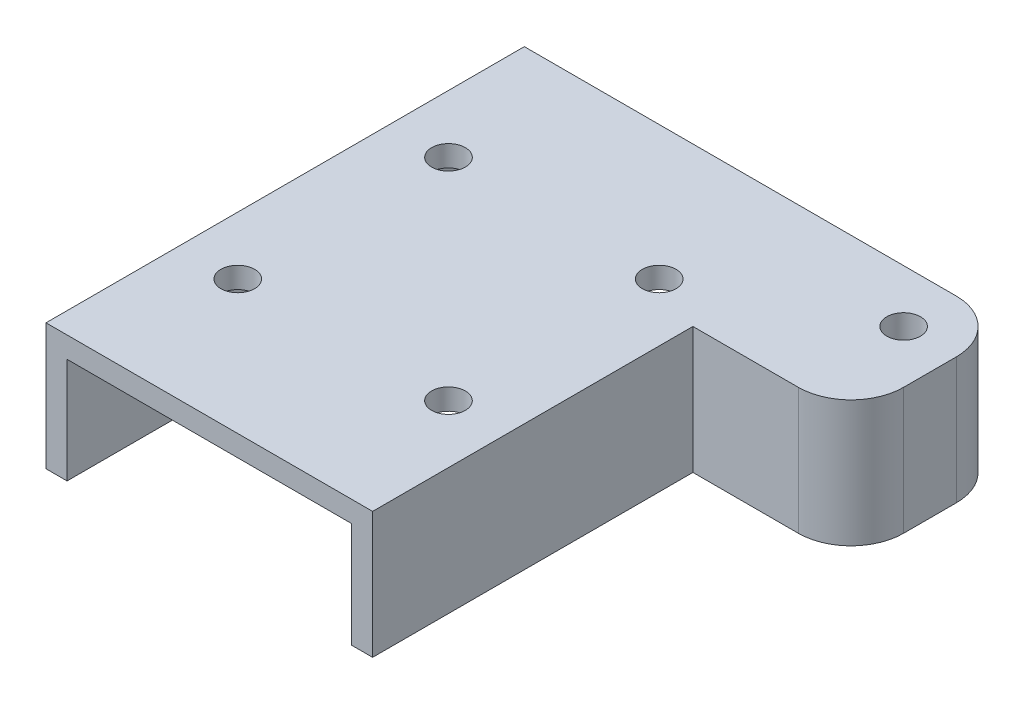
SolidWorks part; units mm, degrees
ref_plane "Front Plane" through (0, 0, 0) normal (0, 0, 1) x (1, 0, 0)
ref_plane "Top Plane" through (0, 0, 0) normal (0, 1, 0) x (1, 0, 0)
ref_plane "Right Plane" through (0, 0, 0) normal (1, 0, 0) x (0, 0, -1)
sketch "Sketch1" plane through (0, 0, 0) normal (0, 1, 0) x (1, 0, 0)
  line L1 (0, 0) -> (31, 0)
  line L2 (0, 0) -> (0, 45.4)
  line L3 (0, 45.4) -> (31, 45.4)
  line L4 (31, 0) -> (31, 45.4)
  dimension "D1" = 31
  dimension "D2" = 45.4
extrude "Boss-Extrude1" add sketch "Sketch1" along normal blind 12
sketch "Sketch2" plane through (0, 0, 0) normal (0, 0, 1) x (1, 0, 0)
  line L0 (0, 0) -> (31, 0) construction
  line L1 (2, 0) -> (29, 0)
  line L2 (2, 0) -> (2, 10)
  line L3 (2, 10) -> (29, 10)
  line L4 (29, 0) -> (29, 10)
  line L5 (0, 12) -> (0, 0) construction
  line L6 (31, 12) -> (31, 0) construction
  dimension "D1" = 2
  dimension "D2" = 2
  dimension "D3" = 10
extrude "Cut-Extrude1" cut sketch "Sketch2" against normal through all
sketch "Sketch3" plane through (0, 12, 0) normal (0, 1, 0) x (1, 0, 0)
  line L0 (15.5, 45.4) -> (15.5, 0) construction
  line L5 (5.5, 12.7) -> (25.5, 12.7) construction
  line L6 (5.5, 12.7) -> (5.5, 32.7) construction
  line L7 (5.5, 32.7) -> (25.5, 32.7) construction
  line L8 (25.5, 12.7) -> (25.5, 32.7) construction
  line L9 (5.5, 12.7) -> (25.5, 32.7) construction
  line L10 (5.5, 32.7) -> (25.5, 12.7) construction
  line L11 (31, 45.4) -> (0, 45.4) construction
  line L12 (0, 0) -> (31, 0) construction
  line L13 (0, 22.7) -> (31, 22.7) construction
  line L14 (0, 45.4) -> (0, 0) construction
  line L15 (31, 0) -> (31, 45.4) construction
  circle A0 centre (5.5, 32.7) radius 1.6
  circle A1 centre (25.5, 32.7) radius 1.6
  circle A2 centre (25.5, 12.7) radius 1.6
  circle A3 centre (5.5, 12.7) radius 1.6
  point P0 (15.5, 22.7)
  dimension "D3" = 3.2
  dimension "D1" = 20
  dimension "D2" = 20
extrude "Cut-Extrude2" cut sketch "Sketch3" against normal blind 10
sketch "Sketch4" plane through (0, 0, 0) normal (-1, 0, 0) x (0, 0, 1)
  line L0 (-45.4, 12) -> (0, 12) construction
  line L1 (-15, 12) -> (0, 12)
  line L2 (-15, 12) -> (-15, 0)
  line L3 (-15, 0) -> (0, 0)
  line L4 (0, 12) -> (0, 0)
  dimension "D1" = 15
extrude "Boss-Extrude2" add sketch "Sketch4" along normal blind 15
sketch "Sketch5" plane through (0, 12, 0) normal (0, 1, 0) x (1, 0, 0)
  line L2 (-15, 0) -> (31, 0) construction
  line L3 (0, 45.4) -> (0, 15) construction
  circle A0 centre (-10, 5) radius 1.6
  dimension "D1" = 3.2
  dimension "D2" = 5
  dimension "D3" = 10
extrude "Cut-Extrude3" cut sketch "Sketch5" against normal blind 20
fillet "Fillet1" radius 5 2 edges at (-15, 6, -15) (-15, 6, 0)
sketch "Sketch6" [suppressed] plane through (31, 0, 0) normal (1, 0, 0) x (0, 0, -1)
  line L9 (5, 0) -> (10, 0)
  line L10 (0, 0) -> (45.4, 0) construction
  line L11 (10, 0) -> (10, 4.7)
  line L12 (10, 4.7) -> (25, 4.7)
  line L13 (25, 4.7) -> (25, 0)
  line L14 (25, 0) -> (30, 0)
  line L15 (30, 0) -> (30, 12)
  line L16 (30, 12) -> (5, 12)
  line L17 (5, 12) -> (5, 0)
  line L18 (0, 12) -> (45.4, 12) construction
  line L19 (0, 12) -> (0, 0) construction
  dimension "D1" = 5
  dimension "D2" = 5
  dimension "D3" = 4.7
  dimension "D4" = 15
  dimension "D5" = 5
extrude "Boss-Extrude3" [suppressed] add sketch "Sketch6" along normal blind 15
chamfer "Chamfer1" [suppressed] distance 5 angle 45
ref_plane "Plane1" [suppressed] through (43, 0, 0) normal (1, 0, 0) x (0, 0, -1)
sketch "Sketch7" [suppressed] plane through (43, 0, 0) normal (1, 0, 0) x (0, 0, -1)
  line L0 (5, 7) -> (15, 12)
  line L1 (5, 12) -> (5, 5) construction
  line L3 (15, 12) -> (5, 12)
  line L4 (5, 12) -> (5, 7)
  line L5 (30, 7) -> (20, 12)
  line L6 (30, 5) -> (30, 12) construction
  line L7 (20, 12) -> (30, 12)
  line L8 (30, 12) -> (30, 7)
  line L9 (30, 12) -> (5, 12) construction
  dimension "D1" = 5
  dimension "D2" = 5
  dimension "D3" = 10
  dimension "D4" = 10
extrude "Cut-Extrude4" [suppressed] cut sketch "Sketch7" against normal blind 4
mirror "Mirror1" [suppressed]
delete or keep bodies "Body-Delete/Keep 1" [suppressed] type delete bodies bodies 111
mirror "Mirror2" about plane through (31, 12, 0) normal (-1, 0, 0) of bodies 105
mirror "Mirror3" about plane through (62, 12, -45.4) normal (0, 0, 1) of bodies 107
delete or keep bodies "Body-Delete/Keep 2" type delete bodies bodies 105 107
mirror "Mirror4" [suppressed]
delete or keep bodies "Body-Delete/Keep 3" [suppressed] type delete bodies bodies 105
